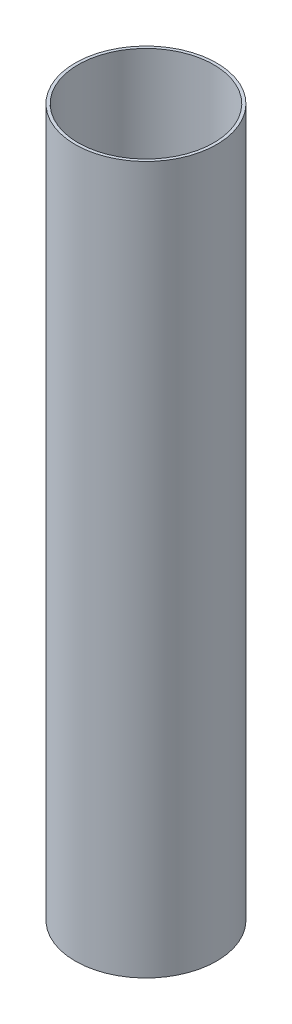
SolidWorks part; units mm, degrees
ref_plane "Front Plane" through (0, 0, 0) normal (0, 0, 1) x (1, 0, 0)
ref_plane "Top Plane" through (0, 0, 0) normal (0, 1, 0) x (1, 0, 0)
ref_plane "Right Plane" through (0, 0, 0) normal (1, 0, 0) x (0, 0, -1)
sketch "Sketch1" plane through (0, 0, 0) normal (0, 1, 0) x (1, 0, 0)
  circle A0 centre (0, 0) radius 76.2
  circle A1 centre (0, 0) radius 73.025
  dimension "D1" = 152.4
  dimension "D2" = 3.175
extrude "Boss-Extrude1" add sketch "Sketch1" along normal blind 762
